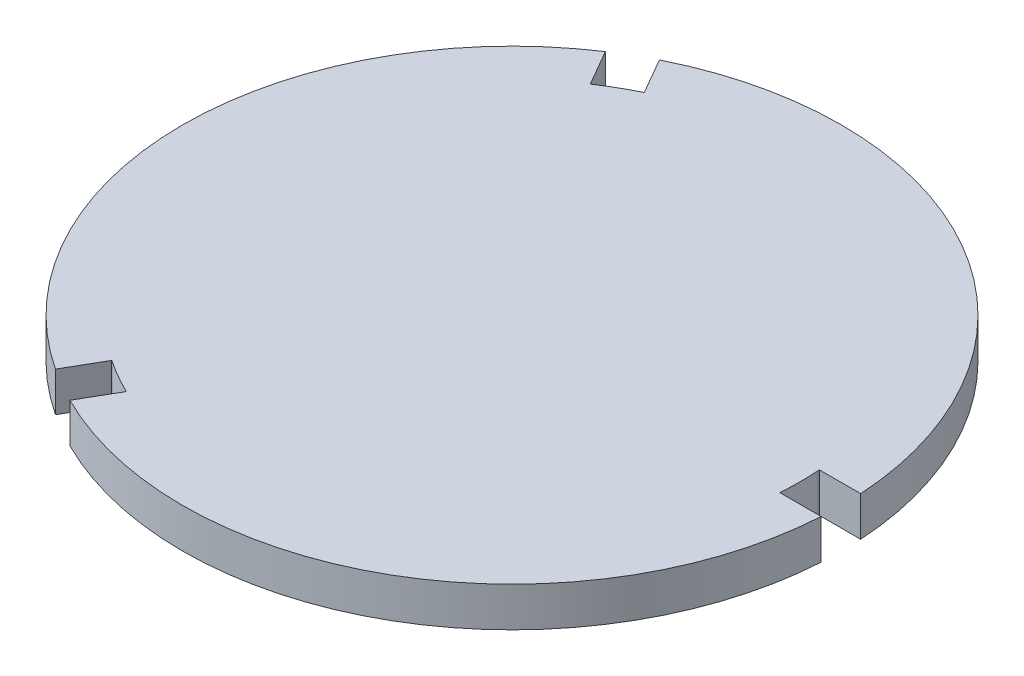
SolidWorks part; units mm, degrees
ref_plane "Front Plane" through (0, 0, 0) normal (0, 0, 1) x (1, 0, 0)
ref_plane "Top Plane" through (0, 0, 0) normal (0, 1, 0) x (1, 0, 0)
ref_plane "Right Plane" through (0, 0, 0) normal (1, 0, 0) x (0, 0, -1)
sketch "Sketch1" plane through (0, 0, 0) normal (0, 0, 1) x (1, 0, 0)
  line L0 (88.9, -136.2802) -> (88.9, -148.4722) construction
  line L1 (-88.9, -136.2802) -> (88.9, -136.2802) construction
  line L2 (-88.9, -148.4722) -> (88.9, -148.4722) construction
  line L3 (88.9, -136.2802) -> (88.9, -148.4722)
  line L4 (0, -136.2802) -> (88.9, -136.2802)
  line L5 (0, -148.4722) -> (88.9, -148.4722)
  line L7 (0, 0) -> (0, -148.4722) construction
  line L9 (0, -136.2802) -> (0, -148.4722)
revolve "Revolve1" add sketch "Sketch1" angle 360 about L7
sketch "Sketch2" plane through (0, -136.2802, 0) normal (0, 1, 0) x (1, 0, 0)
  line L0 (101.417, 6.096) -> (88.717, 6.096)
  line L2 (88.717, 6.096) -> (88.717, -6.096)
  line L3 (101.417, -6.096) -> (88.717, -6.096)
  line L4 (0, 0) -> (88.717, 0) construction
  line L5 (-55.9878, -84.7817) -> (-49.6378, -73.7831)
  line L6 (-39.0792, -79.8791) -> (-49.6378, -73.7831)
  line L7 (-45.4292, -90.8777) -> (-39.0792, -79.8791)
  line L8 (-45.4292, 90.8777) -> (-39.0792, 79.8791)
  line L9 (-49.6378, 73.7831) -> (-39.0792, 79.8791)
  line L10 (-55.9878, 84.7817) -> (-49.6378, 73.7831)
  arc A0 (101.417, 6.096) -> (-45.4292, 90.8777) centre (0, 0) ccw
  arc A2 (-55.9878, 84.7817) -> (-55.9878, -84.7817) centre (0, 0) ccw
  arc A3 (-45.4292, -90.8777) -> (101.417, -6.096) centre (0, 0) ccw
  point P18 (0, 0)
  dimension "D1" = 203.2
  dimension "D2" = 12.192
  dimension "D3" = 12.7
  dimension "D4" = 3
extrude "Boss-Extrude1" add sketch "Sketch2" against normal up to surface (12.192 mm away) contours A2 L5 L6 L7 A3 L3 L2 L0 A0 L8 L9 L10 up to face at (-88.9, -148.4722, 0)
